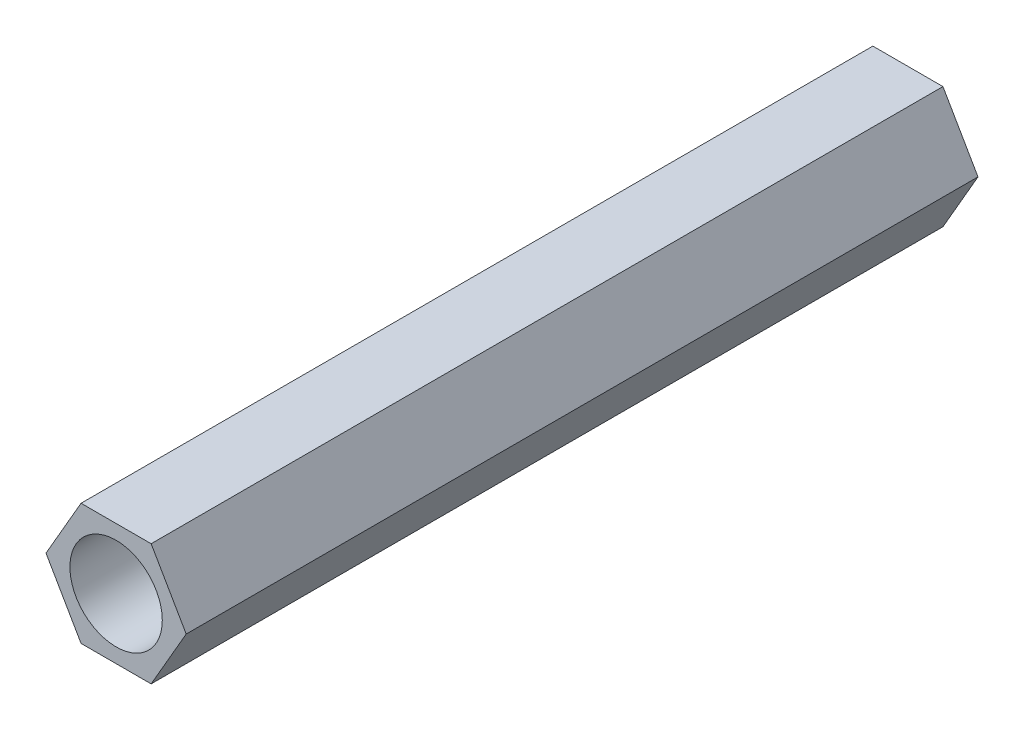
SolidWorks part; units mm, degrees
ref_plane "Alzado" through (0, 0, 0) normal (0, 0, 1) x (1, 0, 0)
ref_plane "Planta" through (0, 0, 0) normal (0, 1, 0) x (1, 0, 0)
ref_plane "Vista lateral" through (0, 0, 0) normal (1, 0, 0) x (0, 0, -1)
sketch "Croquis1" plane through (0, 0, 0) normal (0, 0, 1) x (1, 0, 0)
  line L1 (2.6558, 0) -> (1.3279, 2.3)
  line L2 (1.3279, 2.3) -> (-1.3279, 2.3)
  line L3 (-1.3279, 2.3) -> (-2.6558, 0)
  line L4 (-2.6558, 0) -> (-1.3279, -2.3)
  line L5 (-1.3279, -2.3) -> (1.3279, -2.3)
  line L6 (1.3279, -2.3) -> (2.6558, 0)
  circle A1 centre (0, 0) radius 2.3 construction
  dimension "D1" = 4.6
extrude "Saliente-Extruir1" add sketch "Croquis1" along normal blind 30
ref_point "Punto1"
sketch "Croquis2" plane through (0, 0, 30) normal (0, 0, 1) x (1, 0, 0)
  circle A0 centre (0, 0) radius 1.75
extrude "Cortar-Extruir1" cut sketch "Croquis2" against normal through all
